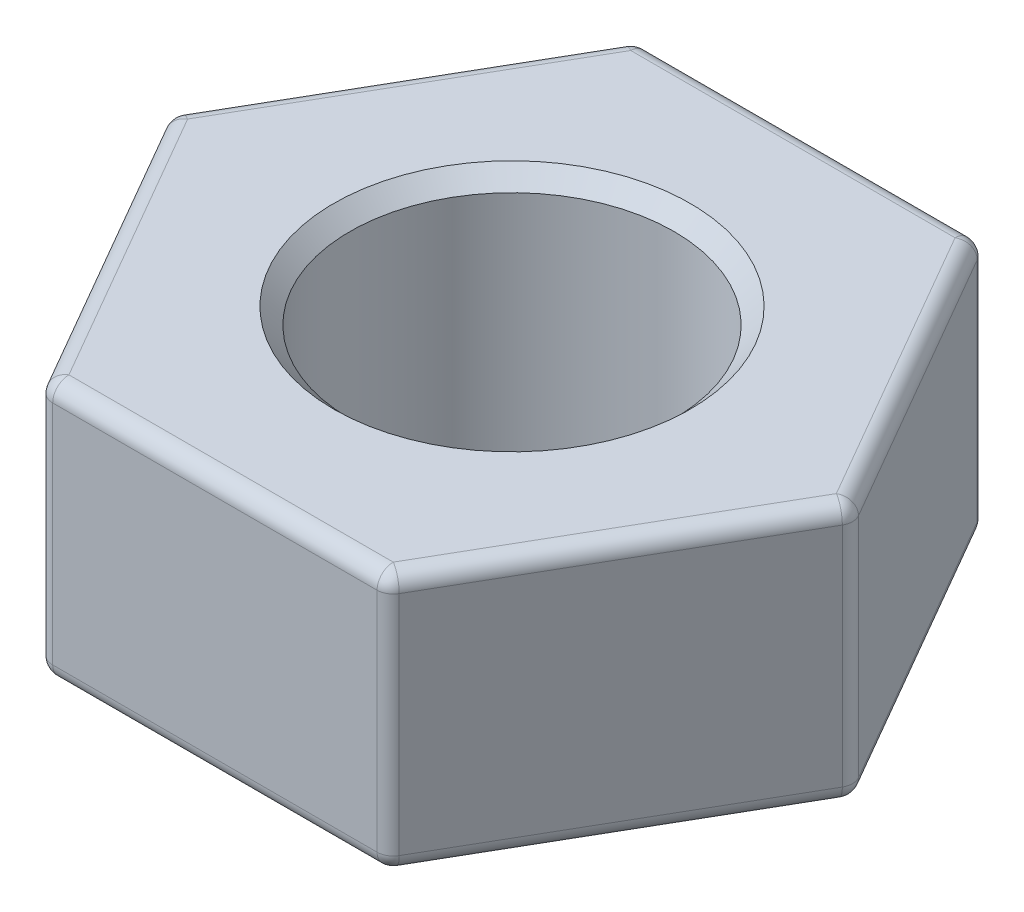
SolidWorks part; units mm, degrees
material "AISI 304"
ref_plane "前视基准面" through (0, 0, 0) normal (0, 0, 1) x (1, 0, 0)
ref_plane "上视基准面" through (0, 0, 0) normal (0, 1, 0) x (1, 0, 0)
ref_plane "右视基准面" through (0, 0, 0) normal (1, 0, 0) x (0, 0, -1)
sketch "草图1" plane through (0, 0, 0) normal (0, 1, 0) x (1, 0, 0)
  line L1 (3.1754, 0) -> (1.5877, 2.75)
  line L2 (1.5877, 2.75) -> (-1.5877, 2.75)
  line L3 (-1.5877, 2.75) -> (-3.1754, 0)
  line L4 (-3.1754, 0) -> (-1.5877, -2.75)
  line L5 (-1.5877, -2.75) -> (1.5877, -2.75)
  line L6 (1.5877, -2.75) -> (3.1754, 0)
  circle A0 centre (0, 0) radius 2.75 construction
  circle A1 centre (0, 0) radius 1.5
  dimension "D2" = 3
  dimension "D1" = 5.5
extrude "凸台-拉伸1" add sketch "草图1" along normal blind 2.4
fillet "圆角1" radius 0.15 18 edges at (2.3816, 0, 1.375) (0, 0, 2.75) (-2.3816, 0, 1.375) (-2.3816, 0, -1.375) (0, 0, -2.75) (2.3816, 0, -1.375) (3.1754, 1.2, 0) (1.5877, 1.2, 2.75) (-1.5877, 1.2, 2.75) (-3.1754, 1.2, 0) (-1.5877, 1.2, -2.75) (1.5877, 1.2, -2.75) (-2.3816, 2.4, 1.375) (-2.3816, 2.4, -1.375) (0, 2.4, -2.75) (2.3816, 2.4, -1.375) (2.3816, 2.4, 1.375) (0, 2.4, 2.75)
chamfer "倒角1" distance 0.15 angle 45 2 edges at (0, 0, 1.5) (0, 2.4, 1.5)
